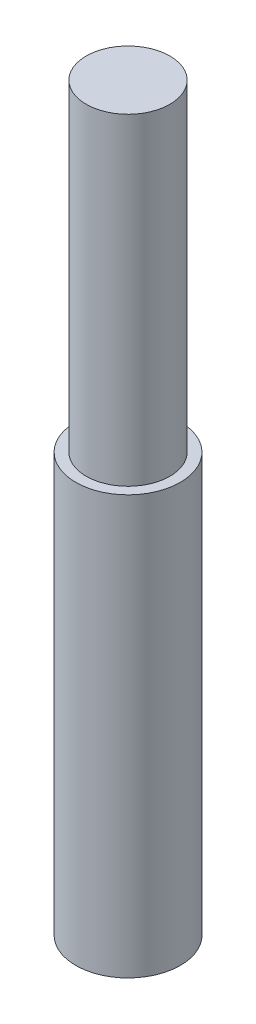
SolidWorks part; units mm, degrees
ref_plane "Ön Düzlem" through (0, 0, 0) normal (0, 0, 1) x (1, 0, 0)
ref_plane "Üst Düzlem" through (0, 0, 0) normal (0, 1, 0) x (1, 0, 0)
ref_plane "Sağ Düzlem" through (0, 0, 0) normal (1, 0, 0) x (0, 0, -1)
sketch "Çizim1" plane through (0, 0, 0) normal (0, 0, 1) x (1, 0, 0)
  line L0 (0, 0) -> (0, 35.4)
  line L1 (0, 35.4) -> (2, 35.4)
  line L2 (2, 35.4) -> (2, 20)
  line L3 (2, 20) -> (2.5, 20)
  line L4 (2.5, 20) -> (2.5, 0)
  line L5 (2.5, 0) -> (0, 0)
  line L6 (2, 28.4) -> (-2, 28.4) construction
  point P3 (2, 28.4)
  dimension "D1" = 7
  dimension "D2" = 2
  dimension "D3" = 2.5
  dimension "D4" = 20
revolve "Döndür1" add sketch "Çizim1" angle 360 about L0
sketch "Çizim2" plane through (0, 0, 0) normal (0, -1, 0) x (1, 0, 0)
  circle A0 centre (0, 0) radius 2
  dimension "D1" = 4
extrude "Kes-Ekstrüzyon1" cut sketch "Çizim2" against normal blind 10
fillet "Radyus1" radius 0.4 1 edges at (0, 0, -2)
